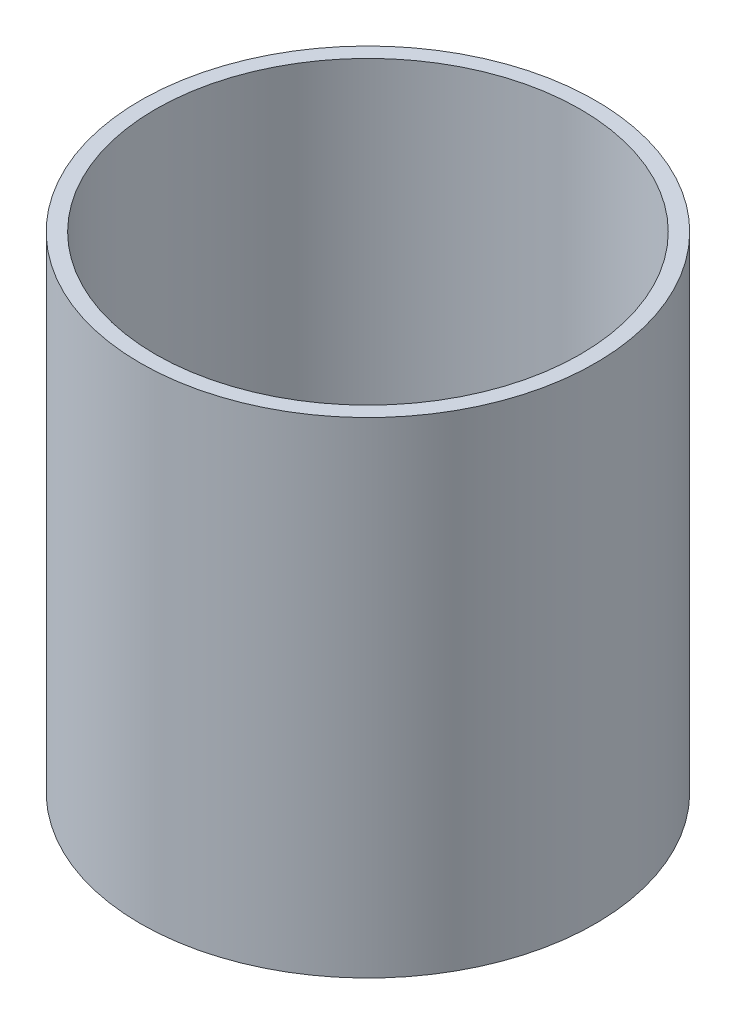
SolidWorks part; units mm, degrees
ref_plane "Front Plane" through (0, 0, 0) normal (0, 0, 1) x (1, 0, 0)
ref_plane "Top Plane" through (0, 0, 0) normal (0, 1, 0) x (1, 0, 0)
ref_plane "Right Plane" through (0, 0, 0) normal (1, 0, 0) x (0, 0, -1)
sketch "Sketch1" plane through (0, 0, 0) normal (0, 0, 1) x (1, 0, 0)
  line L0 (0, 0) -> (48, 0)
  line L1 (48, 0) -> (48, 8)
  line L2 (48, 8) -> (60, 8)
  line L3 (60, 8) -> (60, 136)
  line L4 (60, 136) -> (0, 136)
  line L5 (0, 136) -> (0, 0)
  dimension "D1" = 48
  dimension "D2" = 8
  dimension "D3" = 12
  dimension "D4" = 128
revolve "Goblet Revolve" add sketch "Sketch1" angle 360 about L5
shell "Goblet Shell" thickness 4
sketch "Sketch2" plane through (0, 4, 0) normal (0, 1, 0) x (1, 0, 0)
  circle A0 centre (0, 0) radius 44
extrude "Cut to Fit with Blade Casing" cut sketch "Sketch2" against normal blind 10
